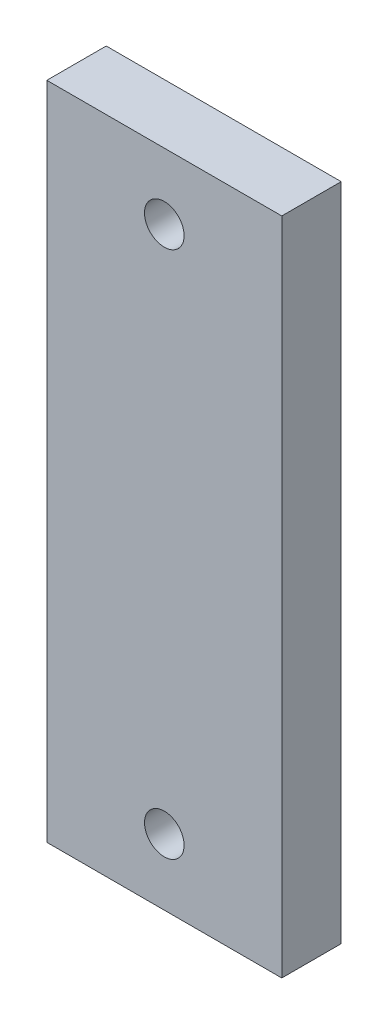
SolidWorks part; units mm, degrees
material "ABS"
ref_plane "前视基准面" through (0, 0, 0) normal (0, 0, 1) x (1, 0, 0)
ref_plane "上视基准面" through (0, 0, 0) normal (0, 1, 0) x (1, 0, 0)
ref_plane "右视基准面" through (0, 0, 0) normal (1, 0, 0) x (0, 0, -1)
sketch "草图1" plane through (0, 0, 0) normal (0, 0, 1) x (1, 0, 0)
  line L0 (0, -25) -> (0, 25) construction
  line L1 (-8.9, -25) -> (8.9, -25)
  line L2 (-8.9, -25) -> (-8.9, 25)
  line L3 (-8.9, 25) -> (8.9, 25)
  line L4 (8.9, -25) -> (8.9, 25)
  line L5 (-8.9, -25) -> (8.9, 25) construction
  line L6 (-8.9, 25) -> (8.9, -25) construction
  circle A0 centre (0, -20) radius 1.5
  circle A1 centre (0, 20) radius 1.5
  point P0 (0, 0)
  dimension "D3" = 3
  dimension "D5" = 5
  dimension "D1" = 17.8
  dimension "D2" = 50
  dimension "D4" = 5
extrude "凸台-拉伸1" add sketch "草图1" along normal blind 4.5
